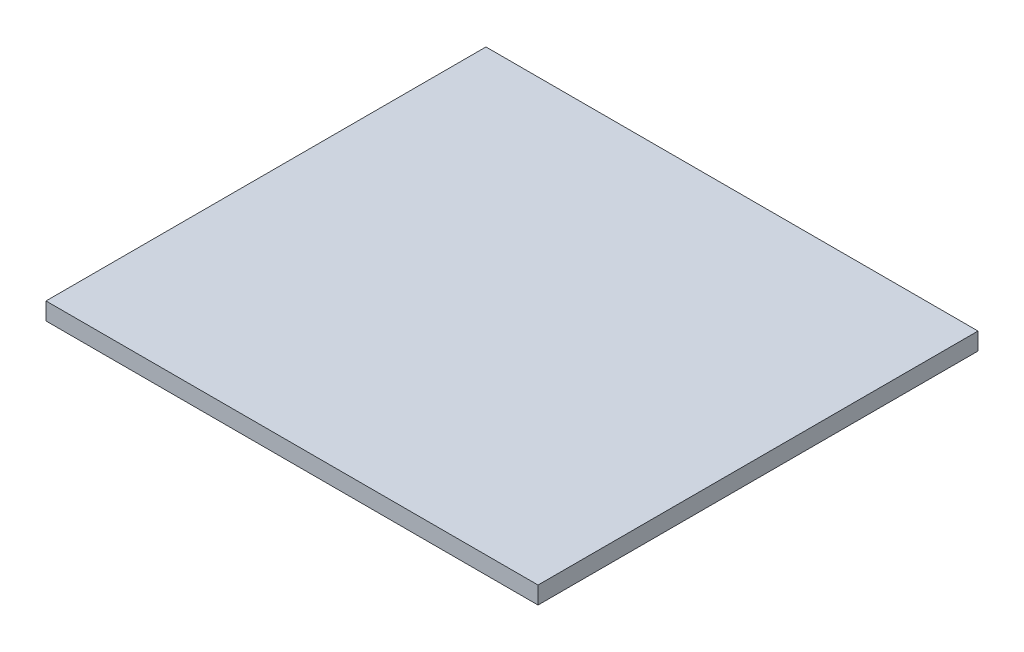
SolidWorks part; units mm, degrees
ref_plane "Front Plane" through (0, 0, 0) normal (0, 0, 1) x (1, 0, 0)
ref_plane "Top Plane" through (0, 0, 0) normal (0, 1, 0) x (1, 0, 0)
ref_plane "Right Plane" through (0, 0, 0) normal (1, 0, 0) x (0, 0, -1)
sketch "Sketch1" plane through (0, 0, 0) normal (0, 1, 0) x (1, 0, 0)
  line L1 (-42.5, -38) -> (42.5, -38)
  line L2 (-42.5, -38) -> (-42.5, 38)
  line L3 (-42.5, 38) -> (42.5, 38)
  line L4 (42.5, -38) -> (42.5, 38)
  line L5 (-42.5, -38) -> (42.5, 38) construction
  line L6 (-42.5, 38) -> (42.5, -38) construction
  point P0 (0, 0)
  dimension "D1" = 85
  dimension "D2" = 76
extrude "Boss-Extrude1" add sketch "Sketch1" along normal blind 3
